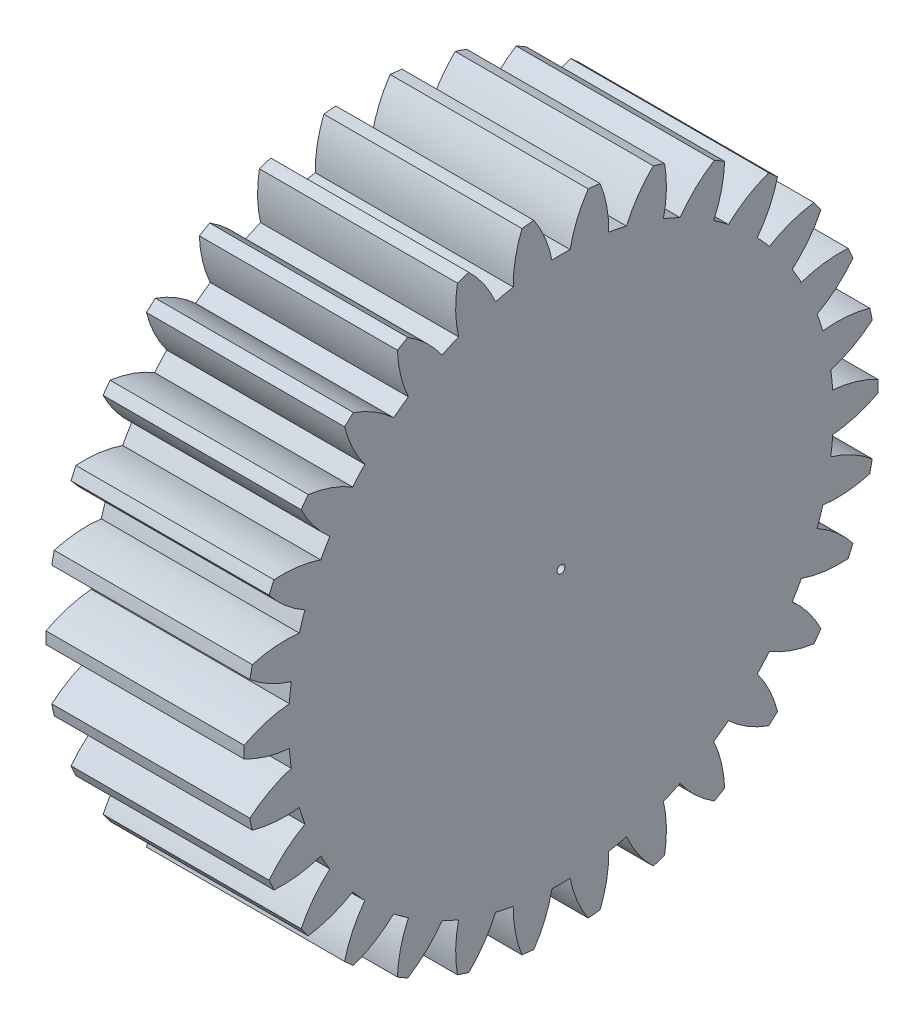
SolidWorks part; units mm, degrees
ref_plane "Plane1" through (0, 0, 0) normal (0, 0, 1) x (1, 0, 0)
ref_plane "Plane2" through (0, 0, 0) normal (0, 1, 0) x (1, 0, 0)
ref_plane "Plane3" through (0, 0, 0) normal (1, 0, 0) x (0, 0, -1)
other "Configuration Table"
sketch "HoldingSke" plane through (0, 0, 0) normal (0, 1, 0) x (1, 0, 0)
  line L0 (0, 0) -> (0.433, -0.25)
  line L1 (-15, 0) -> (100, 0) construction
  line L2 (0, 0) -> (-2.1039, 2.3779)
  line L3 (0, 0) -> (-11.863, 4.5341)
  line L4 (0, 0) -> (7.479, 4.318)
  line L5 (0, 0) -> (-46.8476, -17.4728)
  line L6 (0, 0) -> (-16.5793, -11.1861)
  line L7 (-2.1039, 2.3779) -> (8.6586, 51.2059)
  line L8 (-76.2, 54.61) -> (-76.1, 54.61)
  line L9 (-71.009, 38.7566) -> (-53.1078, 45.2721)
  line L10 (-76.2, 71.12) -> (104.1128, 71.12)
  line L11 (0, 0) -> (-20, 0)
  line L12 (-76.2, 101.6) -> (-76.133, 101.6)
  line L13 (24.9733, 27.94) -> (52.9518, 28.4284)
  line L14 (24.9733, 27.94) -> (24.9743, 27.94)
  line L15 (24.9733, 27.94) -> (100.4006, 29.5858)
  line L16 (-63.627, -2) -> (-12.827, -2)
  circle A0 centre (0, 0) radius 0.4
  circle A1 centre (0, 0) radius 27.499
  circle A2 centre (0, 0) radius 37.5
  circle A3 centre (0, 0) radius 0.4
  dimension "MHD" = 54.998
  dimension "Hub_dia" = 75
  dimension "Bore" = 0.8
  dimension "MBD" = 0.8
  dimension "Num_teeth" = 30
  dimension "Pitch" = 0.5
  dimension "Overall_len" = 50
  dimension "Show_teeth" = 30
  dimension "Thickness" = 20
  dimension "OAL" = 50.0001
  dimension "T_dim" = 0.1
  dimension "Ap" = 20
  dimension "H" = 19.05
  dimension "Pitch_radius" = 180.3128
  dimension "Width" = 20
  dimension "Backlash" = 0.067
  dimension "Addendum_fac" = 1
  dimension "Dedendum_fac" = 1.25
  dimension "Clearance_fac" = 0.25
  dimension "Dedendum_add" = 0.001
  dimension "Module" = 2
sketch "BasProSke" plane through (0, 0, 0) normal (0, 1, 0) x (1, 0, 0)
  line L0 (-10, 0) -> (60, 0) construction
  line L1 (0, 0) -> (0, 32)
  line L2 (0, 0) -> (20, 0)
  line L3 (20, 0) -> (20, 32)
  line L4 (20, 32) -> (0, 32)
  dimension "Thickness" = 20
  dimension "Diameter" = 64
revolve "Base-Revolve" add sketch "BasProSke" angle 360 about L0
sketch "TooCutSke" plane through (0, 0, 0) normal (1, 0, 0) x (0, 0, -1)
  line L1 (0, 0) -> (0, 107) construction
  line L2 (0, 0) -> (-1.6873, 29.9525) construction
  line L3 (0, 0) -> (-6.2643, 59.6013) construction
  line L4 (-1.6873, 29.9525) -> (-3.1322, 29.8007) construction
  arc A0 (0.9186, 27.4837) -> (-0.9186, 27.4837) centre (0, 0) ccw
  arc A1 (2.7618, 31.9061) -> (-2.7618, 31.9061) centre (0, 0) ccw
  circle A2 centre (0, 0) radius 30 construction
  circle A3 centre (0, 0) radius 28.1908 construction
  arc A4 (-0.9186, 27.4837) -> (-2.7618, 31.9061) centre (-12.6936, 25.1712) ccw
  arc A5 (2.7618, 31.9061) -> (0.9186, 27.4837) centre (12.6936, 25.1712) ccw
  dimension "Root_dia" = 54.998
  dimension "Overcut_dia" = 64.0508
  dimension "Pitch_dia" = 60
  dimension "Base_dia" = 56.3816
  dimension "Flank_rad" = 12
  dimension "Half_ang" = 6
  dimension "Half_CT" = 1.4528
extrude "ToothCut" cut sketch "TooCutSke" along normal through all
fillet "Breaks" [suppressed] radius 0.04
fillet "RootFillets" [suppressed] radius 0.501
pattern_circular "TeethCuts" count 30 every 12 about axis through (-10, 0, 0) along (1, 0, 0) of "ToothCut", "RootFillets", "Breaks"
sketch "HubNeaOneSke" plane through (0, 0, 0) normal (-1, 0, 0) x (0, 0, 1)
  circle A0 centre (0, 0) radius 27.499
  dimension "Diameter" = 54.998
extrude "HubNearOne" [suppressed] add sketch "HubNeaOneSke" along normal blind 30.0001
sketch "HubNeaBotSke" plane through (0, 0, 0) normal (-1, 0, 0) x (0, 0, 1)
  circle A0 centre (0, 0) radius 27.499
  dimension "Diameter" = 54.998
extrude "HubNearBoth" [suppressed] add sketch "HubNeaBotSke" along normal blind 15
ref_plane "FarPln" through (20, 0, 0) normal (1, 0, 0) x (0, 0, -1)
sketch "HubFarSke" plane through (20, 0, 0) normal (1, 0, 0) x (0, 0, -1)
  circle A0 centre (0, 0) radius 27.499
  dimension "Diameter" = 54.998
extrude "HubFar" [suppressed] add sketch "HubFarSke" along normal blind 15
sketch "BorSke" plane through (0, 0, 0) normal (1, 0, 0) x (0, 0, -1)
  circle A0 centre (0, 0) radius 0.4
  dimension "Diameter" = 0.8
extrude "Bore" cut sketch "BorSke" along normal mid plane 100.0001
sketch "KeySke" plane through (0, 0, 0) normal (1, 0, 0) x (0, 0, -1)
  line L0 (-0.05, 0) -> (-0.05, 0.5)
  line L1 (-0.05, 0.5) -> (0.05, 0.5)
  line L2 (0.05, 0.5) -> (0.05, 0)
  line L3 (0, 0) -> (0, 34) construction
  line L4 (-0.05, 0) -> (0.05, 0)
  dimension "Offset" = 0.5
  dimension "Width" = 0.1
extrude "Keyway" [suppressed] cut sketch "KeySke" along normal mid plane 100.0001
pattern_circular "Keyway2" [suppressed] count 2 every 90 about axis through (-10, 0, 0) along (1, 0, 0)
equation "' \"Module@HoldingSke\" = 6.35"
equation "' \"Num_teeth@HoldingSke\" = 12"
equation "' \"Ap@HoldingSke\" =  20"
equation "' \"Ap@HoldingSke\" = 20"
equation "' \"Width@HoldingSke\" = 0.5 * 25.4"
equation "' \"Hub_dia@HoldingSke\"= 1 * 25.4"
equation "' \"Hub_dia@HoldingSke\" = 1 * 25.4"
equation "' \"Overall_len@HoldingSke\" = 1.0 * 25.4"
equation "' \"Bore@HoldingSke\" = 0.75 * 25.4"
equation "' \"T_dim@HoldingSke\" = 0.1 * 25.4"
equation "' \"Width@KeySke\" = 0.25 * 25.4"
equation "' \"Show_teeth@HoldingSke\" = 13"
equation "' \"Backlash@HoldingSke\" = 0.009 * 25.4"
equation "' \"Addendum_fac@HoldingSke\" = 1.0"
equation "' \"Dedendum_fac@HoldingSke\" = 1.25"
equation "' \"Dedendum_add@HoldingSke\" = 0.00005 * 25.4"
equation "' \"Clearance_fac@HoldingSke\" = 0.25"
equation "\"Pitch@HoldingSke\" = 1 / \"Module@HoldingSke\""
equation "\"Overcut_dia@TooCutSke\" = (\"Num_teeth@HoldingSke\" + 2 * \"Addendum_fac@HoldingSke\") / \"Pitch@HoldingSke\" + 0.002 * 25.4"
equation "\"Pitch_dia@TooCutSke\" = \"Num_teeth@HoldingSke\" / \"Pitch@HoldingSke\""
equation "\"Base_dia@TooCutSke\" = \"Num_teeth@HoldingSke\" / \"Pitch@HoldingSke\" * cos((\"Ap@HoldingSke\"  * 3.14159265 / 180))"
equation "\"Root_dia@TooCutSke\" = (\"Num_teeth@HoldingSke\" + 2) / \"Pitch@HoldingSke\" - 2 * (\"Addendum_fac@HoldingSke\" + \"Dedendum_fac@HoldingSke\") / \"Pitch@HoldingSke\" - \"Dedendum_add@HoldingSke\" * 2"
equation "\"Half_ang@TooCutSke\" = 180 / \"Num_teeth@HoldingSke\""
equation "\"Half_CT@TooCutSke\" = \"Num_teeth@HoldingSke\" / \"Pitch@HoldingSke\" * sin((3.14159265 / 2 / \"Num_teeth@HoldingSke\")) / 2 - 7 * \"Backlash@HoldingSke\" / 4"
equation "\"Flank_rad@TooCutSke\" = \"Num_teeth@HoldingSke\" / \"Pitch@HoldingSke\" / 5"
equation "\"Radius@RootFillets\" = \"Clearance_fac@HoldingSke\" / \"Pitch@HoldingSke\" + \"Dedendum_add@HoldingSke\""
equation "\"Break_rad@Breaks\" = 0.02 / \"Pitch@HoldingSke\""
equation "\"Thickness@HoldingSke\" = \"Width@HoldingSke\""
equation "\"OAL@HoldingSke\" = \"Thickness@HoldingSke\""
equation "\"MHD@HoldingSke\" = (\"Num_teeth@HoldingSke\" + 2) / \"Pitch@HoldingSke\" - 2 * (\"Addendum_fac@HoldingSke\" + \"Dedendum_fac@HoldingSke\")  / \"Pitch@HoldingSke\" - \"Dedendum_add@HoldingSke\" * 2"
equation "\"MBD@HoldingSke\" = (\"Num_teeth@HoldingSke\" + 2) / \"Pitch@HoldingSke\" - 2 * (\"Addendum_fac@HoldingSke\" + \"Dedendum_fac@HoldingSke\")  / \"Pitch@HoldingSke\" - \"Dedendum_add@HoldingSke\" * 2 - 0.002 * 25.4"
equation "\"MHD@HoldingSke\" = ((sgn( \"MHD@HoldingSke\" - \"Hub_dia@HoldingSke\" )-1)*( \"MHD@HoldingSke\" - \"Hub_dia@HoldingSke\" ))/-2+ \"Hub_dia@HoldingSke\""
equation "\"MBD@HoldingSke\" = ((sgn( \"MBD@HoldingSke\" - \"Bore@HoldingSke\" )-1)*( \"MBD@HoldingSke\" - \"Bore@HoldingSke\" ))/-2+ \"Bore@HoldingSke\""
equation "\"OAL@HoldingSke\" = ((sgn( \"OAL@HoldingSke\" - \"Overall_len@HoldingSke\" )+1)*( \"OAL@HoldingSke\" - \"Overall_len@HoldingSke\" ))/2 + \"Overall_len@HoldingSke\" + 0.000002 * 25.4"
equation "\"Num_teeth@TeethCuts\" = int( \"Show_teeth@HoldingSke\" ) + 1"
equation "\"Num_teeth@TeethCuts\" = ((sgn( \"Num_teeth@TeethCuts\" - \"Num_teeth@HoldingSke\" )-1)*( \"Num_teeth@TeethCuts\" - \"Num_teeth@HoldingSke\" ))/-2+ \"Num_teeth@HoldingSke\""
equation "\"Num_teeth@TeethCuts\" = ((sgn( \"Num_teeth@TeethCuts\" - 2.0)+1)*( \"Num_teeth@TeethCuts\" - 2.0))/2 +2.0"
equation "\"Angle@TeethCuts\" = 360.0 / \"Num_teeth@HoldingSke\""
equation "\"Diameter@BasProSke\" = (\"Num_teeth@HoldingSke\" + 2 * \"Addendum_fac@HoldingSke\") / \"Pitch@HoldingSke\""
equation "\"Thickness@BasProSke\"  = \"Thickness@HoldingSke\""
equation "' \"Fillet_rad@BasProSke\" =  \"Thickness@HoldingSke\" * 0.05"
equation "' \"Fillet_rad@BasProSke\" = \"Thickness@HoldingSke\" * 0.05"
equation "\"MHD@HoldingSke\" = ((sgn( \"MHD@HoldingSke\" - \"Root_dia@TooCutSke\" )-1)*( \"MHD@HoldingSke\" - \"Root_dia@TooCutSke\" ))/-2+ \"Root_dia@TooCutSke\""
equation "\"Diameter@HubNeaOneSke\" = \"MHD@HoldingSke\""
equation "\"Length@HubNearOne\" = \"OAL@HoldingSke\" - \"Thickness@BasProSke\""
equation "\"Diameter@HubNeaBotSke\" = \"MHD@HoldingSke\""
equation "\"Length@HubNearBoth\" = ( \"OAL@HoldingSke\" - \"Thickness@BasProSke\" ) / 2.0"
equation "\"Thickness@FarPln\" = \"Thickness@BasProSke\""
equation "\"Diameter@HubFarSke\" = \"MHD@HoldingSke\""
equation "\"Length@HubFar\" = ( \"OAL@HoldingSke\" - \"Thickness@BasProSke\" ) / 2.0"
equation "\"Diameter@BorSke\" = \"MBD@HoldingSke\""
equation "\"D1@Bore\" = \"OAL@HoldingSke\" * 2.0"
equation "\"D1@Keyway\" = \"OAL@HoldingSke\" * 2.0"
equation "\"Offset@KeySke\" = \"T_dim@HoldingSke\" + \"MBD@HoldingSke\" / 2.0"
